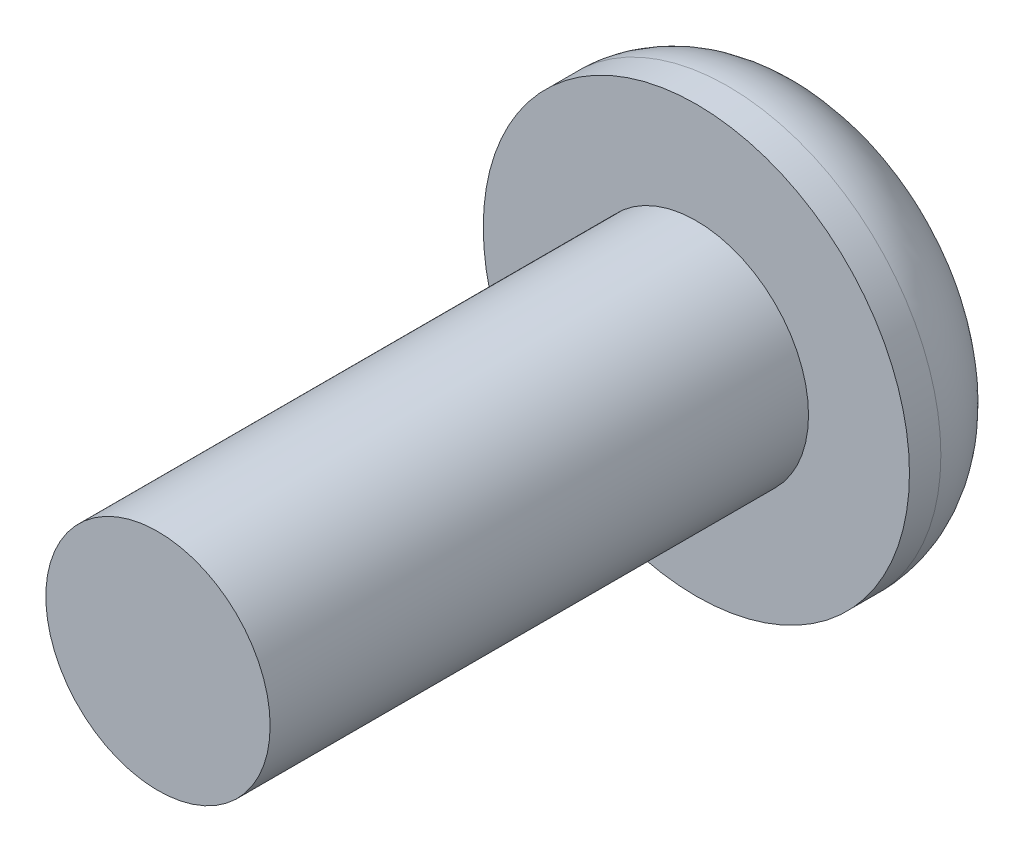
SolidWorks part; units mm, degrees
ref_plane "前视基准面" through (0, 0, 0) normal (0, 0, 1) x (1, 0, 0)
ref_plane "上视基准面" through (0, 0, 0) normal (0, 1, 0) x (1, 0, 0)
ref_plane "右视基准面" through (0, 0, 0) normal (1, 0, 0) x (0, 0, -1)
sketch "草图1" plane through (0, 0, 0) normal (0, 0, 1) x (1, 0, 0)
  circle A0 centre (0, 0) radius 2.5
  dimension "D1" = 5
extrude "凸台-拉伸1" add sketch "草图1" along normal blind 12
sketch "草图2" plane through (0, 0, 0) normal (0, 0, -1) x (-1, 0, 0)
  circle A0 centre (0, 0) radius 4.75
  dimension "D1" = 9.5
extrude "凸台-拉伸2" add sketch "草图2" along normal blind 2.7
fillet "圆角1" radius 2 1 edges at (-4.75, 0, -2.7)
sketch "草图3" plane through (0, 0, -2.7) normal (0, 0, -1) x (-1, 0, 0)
  line L1 (1.4686, 0.9183) -> (-0.061, 1.731)
  line L2 (-0.061, 1.731) -> (-1.5296, 0.8127)
  line L3 (-1.5296, 0.8127) -> (-1.4686, -0.9183)
  line L4 (-1.4686, -0.9183) -> (0.061, -1.731)
  line L5 (0.061, -1.731) -> (1.5296, -0.8127)
  line L6 (1.5296, -0.8127) -> (1.4686, 0.9183)
  circle A0 centre (0, 0) radius 1.5 construction
  dimension "D1" = 3
extrude "切除-拉伸1" cut sketch "草图3" against normal blind 1.56
